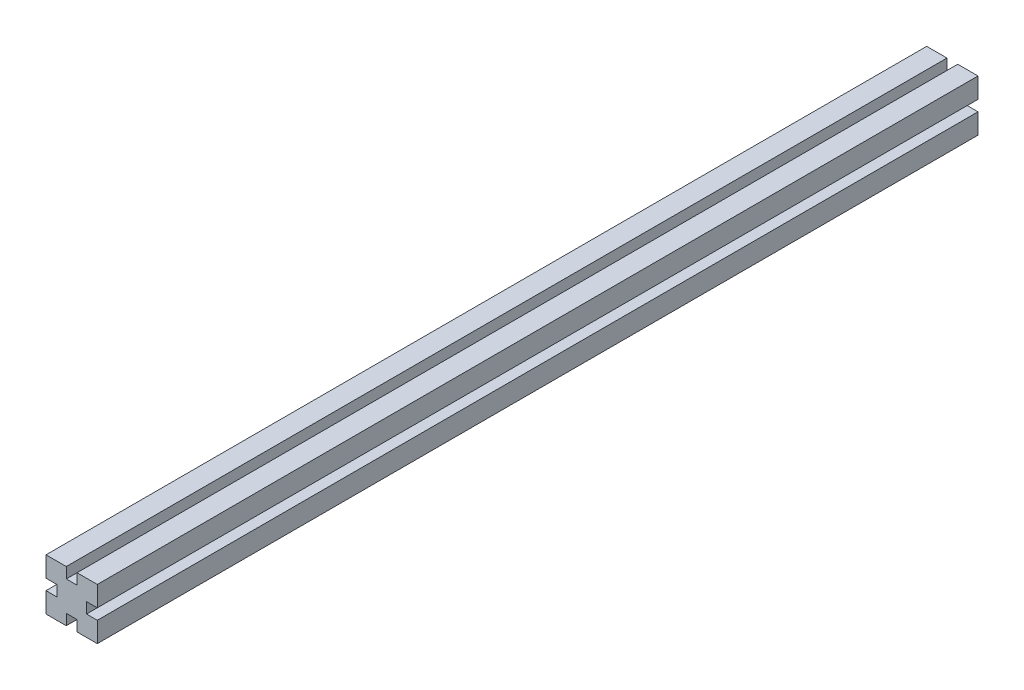
SolidWorks part; units mm, degrees
ref_plane "Front Plane" through (0, 0, 0) normal (0, 0, 1) x (1, 0, 0)
ref_plane "Top Plane" through (0, 0, 0) normal (0, 1, 0) x (1, 0, 0)
ref_plane "Right Plane" through (0, 0, 0) normal (1, 0, 0) x (0, 0, -1)
sketch "Sketch1" plane through (0, 0, 0) normal (0, 0, 1) x (1, 0, 0)
  line L0 (-19.05, -19.05) -> (-4, -19.05)
  line L1 (-4, -19.05) -> (-4, -11.05)
  line L2 (-4, -11.05) -> (4, -11.05)
  line L3 (4, -11.05) -> (4, -19.05)
  line L4 (4, -19.05) -> (19.05, -19.05)
  line L5 (19.05, -19.05) -> (19.05, -4)
  line L6 (19.05, -4) -> (11.05, -4)
  line L7 (11.05, -4) -> (11.05, 4)
  line L8 (11.05, 4) -> (19.05, 4)
  line L9 (19.05, 4) -> (19.05, 19.05)
  line L10 (19.05, 19.05) -> (4, 19.05)
  line L11 (4, 19.05) -> (4, 11.05)
  line L12 (4, 11.05) -> (-4, 11.05)
  line L13 (-4, 11.05) -> (-4, 19.05)
  line L14 (-4, 19.05) -> (-19.05, 19.05)
  line L15 (-19.05, 19.05) -> (-19.05, 4)
  line L16 (-19.05, 4) -> (-11.05, 4)
  line L17 (-11.05, 4) -> (-11.05, -4)
  line L18 (-11.05, -4) -> (-19.05, -4)
  line L19 (-19.05, -4) -> (-19.05, -19.05)
extrude "Profile" add sketch "Sketch1" along normal blind 654.05
equation "\"length\" = 654.05mm"
equation "\"D1@Profile\" = \"length\""
